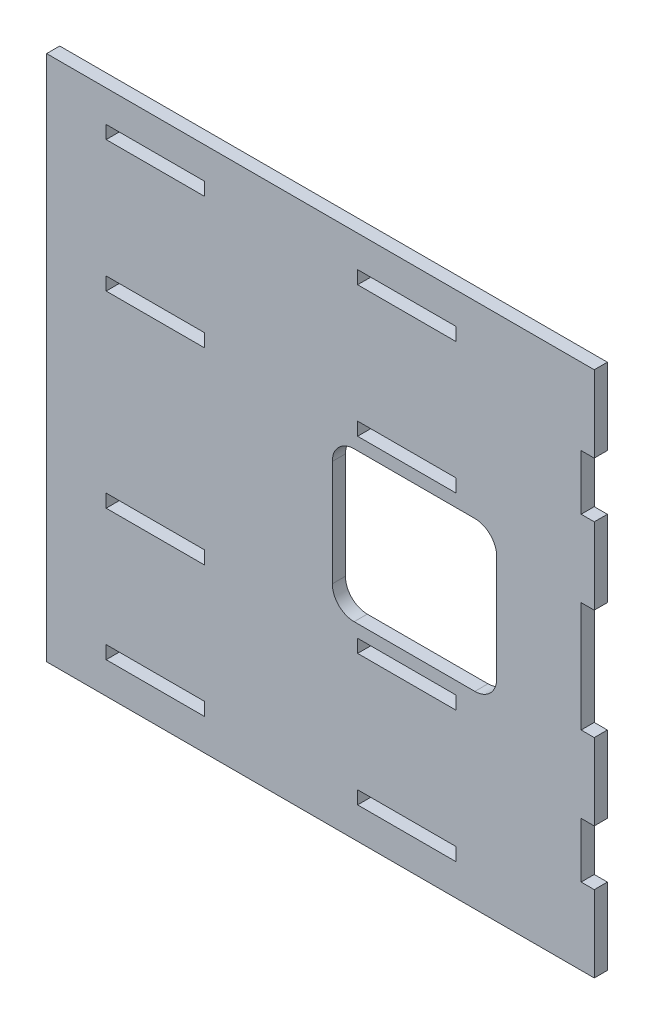
SolidWorks part; units mm, degrees
ref_plane "Front Plane" through (0, 0, 0) normal (0, 0, 1) x (1, 0, 0)
ref_plane "Top Plane" through (0, 0, 0) normal (0, 1, 0) x (1, 0, 0)
ref_plane "Right Plane" through (0, 0, 0) normal (1, 0, 0) x (0, 0, -1)
sketch "Sketch1" plane through (0, 0, 0) normal (0, 0, 1) x (1, 0, 0)
  line L0 (-59.2512, -240.5581) -> (-14.2512, -240.5581)
  line L1 (127.9726, -160.1085) -> (-86.4749, -160.1085)
  line L3 (127.9726, -401.0078) -> (-86.4749, -401.0078)
  line L4 (-86.4749, -160.1085) -> (-86.4749, -401.0078)
  line L13 (-59.2512, -240.5581) -> (-59.2512, -234.5581)
  line L14 (-59.2512, -234.5581) -> (-14.2512, -234.5581)
  line L15 (-14.2512, -240.5581) -> (-14.2512, -234.5581)
  line L16 (55.7488, -234.5581) -> (100.7488, -234.5581)
  line L17 (55.7488, -234.5581) -> (55.7488, -240.5581)
  line L18 (55.7488, -240.5581) -> (100.7488, -240.5581)
  line L19 (100.7488, -234.5581) -> (100.7488, -240.5581)
  line L32 (-59.2512, -180.5581) -> (-14.2512, -180.5581)
  line L33 (-59.2512, -180.5581) -> (-59.2512, -174.5581)
  line L34 (-59.2512, -174.5581) -> (-14.2512, -174.5581)
  line L35 (-14.2512, -180.5581) -> (-14.2512, -174.5581)
  line L36 (55.7488, -174.5581) -> (100.7488, -174.5581)
  line L37 (55.7488, -174.5581) -> (55.7488, -180.5581)
  line L38 (55.7488, -180.5581) -> (100.7488, -180.5581)
  line L39 (100.7488, -174.5581) -> (100.7488, -180.5581)
  line L40 (-59.2512, -386.5581) -> (-14.2512, -386.5581)
  line L41 (-59.2512, -386.5581) -> (-59.2512, -380.5581)
  line L42 (-59.2512, -380.5581) -> (-14.2512, -380.5581)
  line L43 (-14.2512, -386.5581) -> (-14.2512, -380.5581)
  line L44 (55.7488, -380.5581) -> (100.7488, -380.5581)
  line L45 (55.7488, -380.5581) -> (55.7488, -386.5581)
  line L46 (55.7488, -386.5581) -> (100.7488, -386.5581)
  line L47 (100.7488, -380.5581) -> (100.7488, -386.5581)
  line L49 (100.7488, -326.5581) -> (100.7488, -320.5581)
  line L50 (55.7488, -320.5581) -> (100.7488, -320.5581)
  line L51 (55.7488, -326.5581) -> (55.7488, -320.5581)
  line L52 (55.7488, -326.5581) -> (100.7488, -326.5581)
  line L53 (-14.2512, -320.5581) -> (-14.2512, -326.5581)
  line L54 (-59.2512, -326.5581) -> (-14.2512, -326.5581)
  line L55 (-59.2512, -320.5581) -> (-59.2512, -326.5581)
  line L56 (-59.2512, -320.5581) -> (-14.2512, -320.5581)
  line L57 (54.1677, -246.3241) -> (109.37, -246.3241)
  line L58 (44.1677, -256.3241) -> (44.1677, -304.7922)
  line L59 (54.1677, -314.7922) -> (109.37, -314.7922)
  line L60 (119.37, -256.3241) -> (119.37, -304.7922)
  line L62 (127.9726, -160.1085) -> (157.9726, -160.1085)
  line L64 (127.9726, -401.0078) -> (157.9726, -401.0078)
  line L65 (157.9726, -195.1085) -> (157.9726, -220.3333)
  line L67 (157.9726, -160.1085) -> (163.9726, -160.1085)
  line L69 (157.9726, -195.1085) -> (163.9726, -195.1085)
  line L70 (163.9726, -160.1085) -> (163.9726, -195.1085)
  line L72 (163.9726, -340.7829) -> (163.9726, -305.7829)
  line L73 (157.9726, -255.3333) -> (157.9726, -305.7829)
  line L74 (157.9726, -220.3333) -> (163.9726, -220.3333)
  line L76 (157.9726, -255.3333) -> (163.9726, -255.3333)
  line L77 (163.9726, -220.3333) -> (163.9726, -255.3333)
  line L78 (157.9726, -305.7829) -> (163.9726, -305.7829)
  line L79 (157.9726, -340.7829) -> (163.9726, -340.7829)
  line L81 (163.9726, -401.0078) -> (163.9726, -366.0078)
  line L82 (157.9726, -366.0078) -> (163.9726, -366.0078)
  line L83 (157.9726, -401.0078) -> (163.9726, -401.0078)
  line L84 (157.9726, -366.0078) -> (157.9726, -340.7829)
  arc A0 (44.1677, -304.7922) -> (54.1677, -314.7922) centre (54.1677, -304.7922) ccw
  arc A1 (109.37, -314.7922) -> (119.37, -304.7922) centre (109.37, -304.7922) ccw
  arc A2 (109.37, -246.3241) -> (119.37, -256.3241) centre (109.37, -256.3241) cw
  arc A3 (54.1677, -246.3241) -> (44.1677, -256.3241) centre (54.1677, -256.3241) ccw
  point P20 (81.7689, -280.5581)
  point P59 (160.9726, -237.8333)
  point P68 (160.9726, -323.2829)
  dimension "D1" = 10
  dimension "D2" = 240.8992
  dimension "D3" = 6
  dimension "D4" = 30
  dimension "D6" = 0
  dimension "D7" = 6
  dimension "D8" = 35
  dimension "D9" = 35
extrude "Boss-Extrude1" add sketch "Sketch1" along normal blind 6
